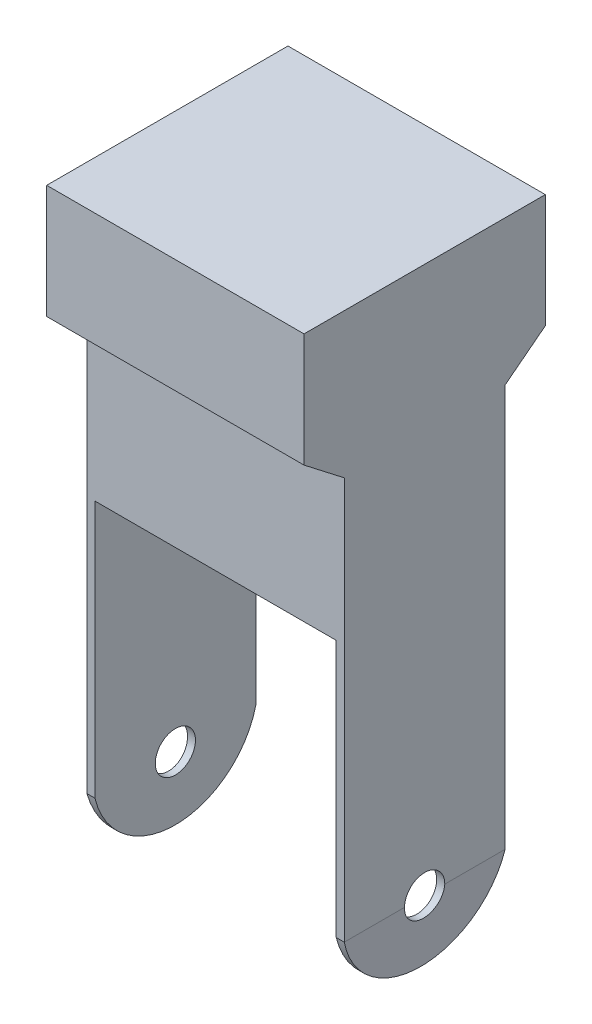
SolidWorks part; units mm, degrees
ref_plane "Front Plane" through (0, 0, 0) normal (0, 0, 1) x (1, 0, 0)
ref_plane "Top Plane" through (0, 0, 0) normal (0, 1, 0) x (1, 0, 0)
ref_plane "Right Plane" through (0, 0, 0) normal (1, 0, 0) x (0, 0, -1)
sketch "Sketch1" plane through (0, 0, 0) normal (0, 0, 1) x (1, 0, 0)
  line L0 (0, 0) -> (0, 68) construction
  line L1 (-15, 0) -> (15, 0) construction
  line L2 (0, 0) -> (0, -8) construction
  line L3 (-15, -8) -> (-15, 32)
  line L4 (-15, 32) -> (15, 32)
  line L5 (15, 32) -> (15, -8)
  line L6 (15, -8) -> (15.5, -8)
  line L7 (16, 0) -> (16, 68)
  line L8 (-15, -8) -> (-15.5, -8)
  line L9 (-16, 0) -> (-16, 68)
  line L10 (-16, 68) -> (16, 68)
  line L11 (-15.5, -8) -> (-16, 0)
  line L12 (15.5, -8) -> (16, 0)
  point P6 (0, 0)
extrude "Boss-Extrude1" add sketch "Sketch1" along normal mid plane 30
sketch "Sketch3" plane through (-16, 0, 0) normal (-1, 0, 0) x (0, 0, 1)
  line L0 (15, 0) -> (-15, 0) construction
  line L1 (0, 0) -> (-10, 0) construction
  line L2 (-10, 0) -> (-10, 50)
  line L3 (-10, 50) -> (-16.3259, 54.8972)
  line L4 (-16.3259, 54.8972) -> (-25.1928, 54.8972)
  line L5 (-25.1928, 54.8972) -> (-25.1928, -12.9838)
  line L6 (0, -0.9443) -> (0, 33.0495) construction
  line L7 (10, 50) -> (16.3259, 54.8972)
  line L8 (10, 0) -> (10, 50)
  line L9 (16.3259, 54.8972) -> (26.3259, 54.8972)
  line L10 (26.3259, 54.8972) -> (26.3259, -12.9838)
  line L11 (26.3259, -12.9838) -> (-25.1928, -12.9838)
  circle A0 centre (0, 0) radius 2.5
  arc A1 (-10, 0) -> (10, 0) centre (0, 2.4121) ccw
extrude "Cut-Extrude1" cut sketch "Sketch3" against normal through all both and the other way through all
